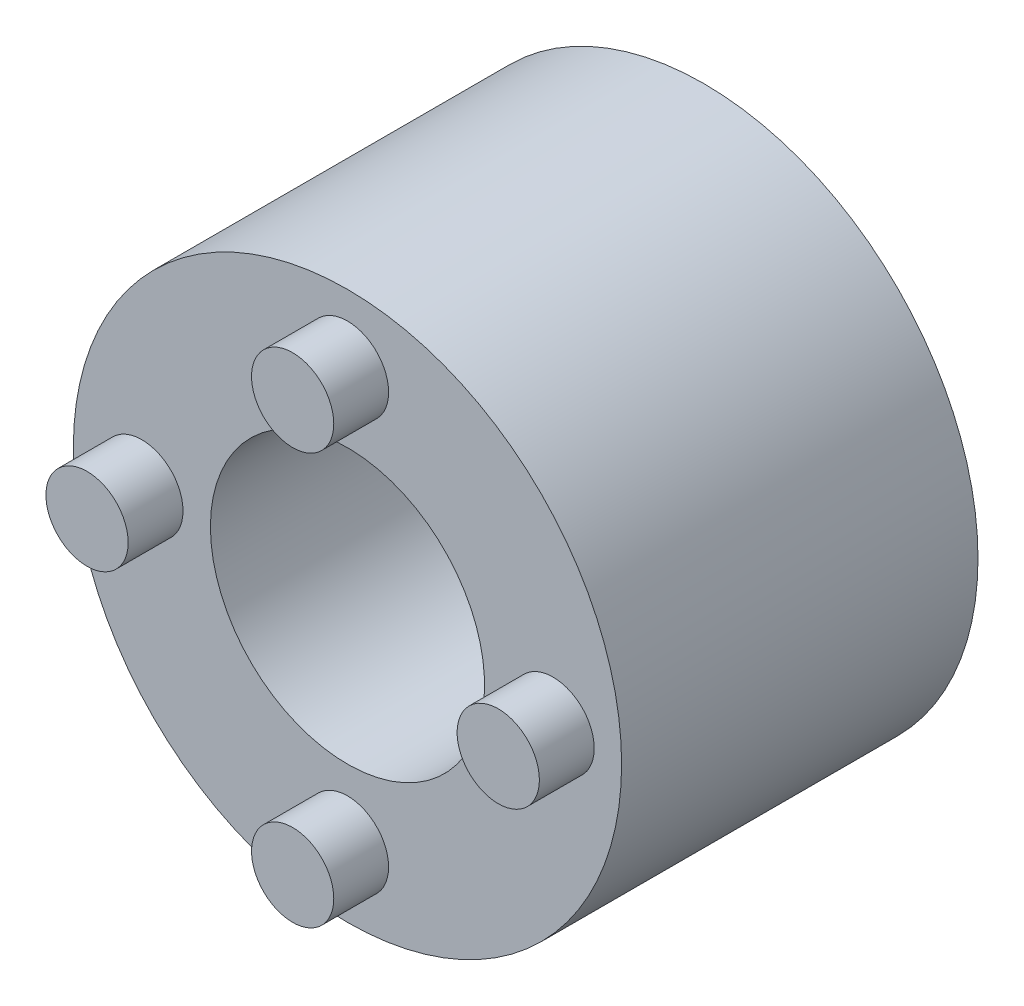
SolidWorks part; units mm, degrees
material "合金钢 (SS)"
ref_plane "前视基准面" through (0, 0, 0) normal (0, 0, 1) x (1, 0, 0)
ref_plane "上视基准面" through (0, 0, 0) normal (0, 1, 0) x (1, 0, 0)
ref_plane "右视基准面" through (0, 0, 0) normal (1, 0, 0) x (0, 0, -1)
sketch "草图1" plane through (0, 0, 0) normal (0, 0, 1) x (1, 0, 0)
  circle A0 centre (0, 0) radius 5
  circle A1 centre (0, 0) radius 10
  dimension "D1" = 10
  dimension "D2" = 20
extrude "凸台-拉伸1" add sketch "草图1" along normal mid plane 13
sketch "草图2" plane through (0, 0, 6.5) normal (0, 0, 1) x (1, 0, 0)
  circle A0 centre (0, 0) radius 7.5 construction
  circle A1 centre (0, 7.5) radius 1.5
  circle A2 centre (7.5, 0) radius 1.5
  circle A3 centre (0, -7.5) radius 1.5
  circle A4 centre (-7.5, 0) radius 1.5
  point P5 (-0.0912, -10.8104)
  point P6 (0, 0)
  point P14 (0, 0)
  dimension "D1" = 15
  dimension "D2" = 3
  dimension "D3" = 4
extrude "凸台-拉伸2" add sketch "草图2" along normal mid plane 4
